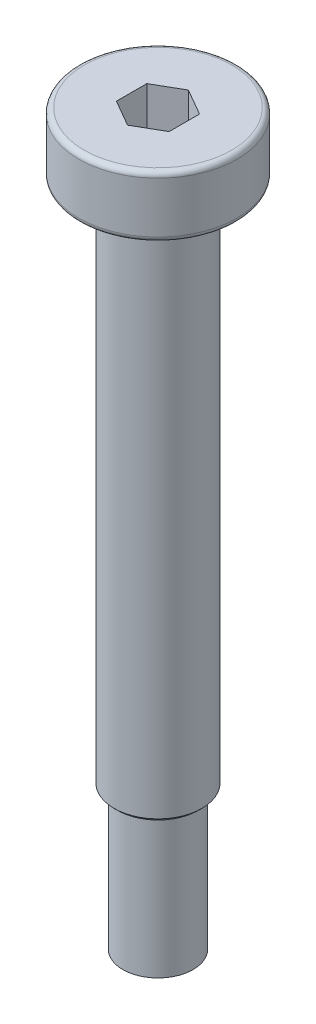
SolidWorks part; units mm, degrees
ref_plane "前视基准面" through (0, 0, 0) normal (0, 0, 1) x (1, 0, 0)
ref_plane "上视基准面" through (0, 0, 0) normal (0, 1, 0) x (1, 0, 0)
ref_plane "右视基准面" through (0, 0, 0) normal (1, 0, 0) x (0, 0, -1)
sketch "草图1" plane through (0, 0, 0) normal (0, 0, 1) x (1, 0, 0)
  line L0 (0, 13.2929) -> (0, -24.3848) construction
  line L1 (0, 9.6164) -> (-4.5, 9.6164)
  line L2 (-4.5, 9.6164) -> (-4.5, 6.1164)
  line L3 (-4.5, 6.1164) -> (-2.5, 6.1164)
  line L4 (-2.5, 6.1164) -> (-2.5, -23.8836)
  line L5 (-2.5, -23.8836) -> (-2, -23.8836)
  line L6 (-2, -23.8836) -> (-2, -31.8836)
  line L7 (-2, -31.8836) -> (0, -31.8836)
  line L8 (0, 9.6164) -> (0, -31.8836)
  point P6 (0, 13.2929)
  point P13 (0, -24.3848)
  dimension "D1" = 4
  dimension "D2" = 8
  dimension "D3" = 5
  dimension "D4" = 9
  dimension "D5" = 3.5
  dimension "D6" = 30
revolve "旋转1" add sketch "草图1" angle 360 about L0
cosmetic thread "装饰螺纹线1" parameters "D2"=3.242
fillet "圆角1" radius 0.3 2 edges at (0, 6.1164, 4.5) (0, 9.6164, 4.5)
sketch "草图2" plane through (0, 9.6164, 0) normal (0, 1, 0) x (1, 0, 0)
  line L1 (1.5, 0.866) -> (0, 1.7321)
  line L2 (0, 1.7321) -> (-1.5, 0.866)
  line L3 (-1.5, 0.866) -> (-1.5, -0.866)
  line L4 (-1.5, -0.866) -> (0, -1.7321)
  line L5 (0, -1.7321) -> (1.5, -0.866)
  line L6 (1.5, -0.866) -> (1.5, 0.866)
  circle A0 centre (0, 0) radius 1.5 construction
  dimension "D1" = 3
extrude "切除-拉伸1" cut sketch "草图2" against normal blind 2.4
chamfer "倒角1" distance 0.2 angle 45 1 edges at (0, -23.8836, 2.5)
